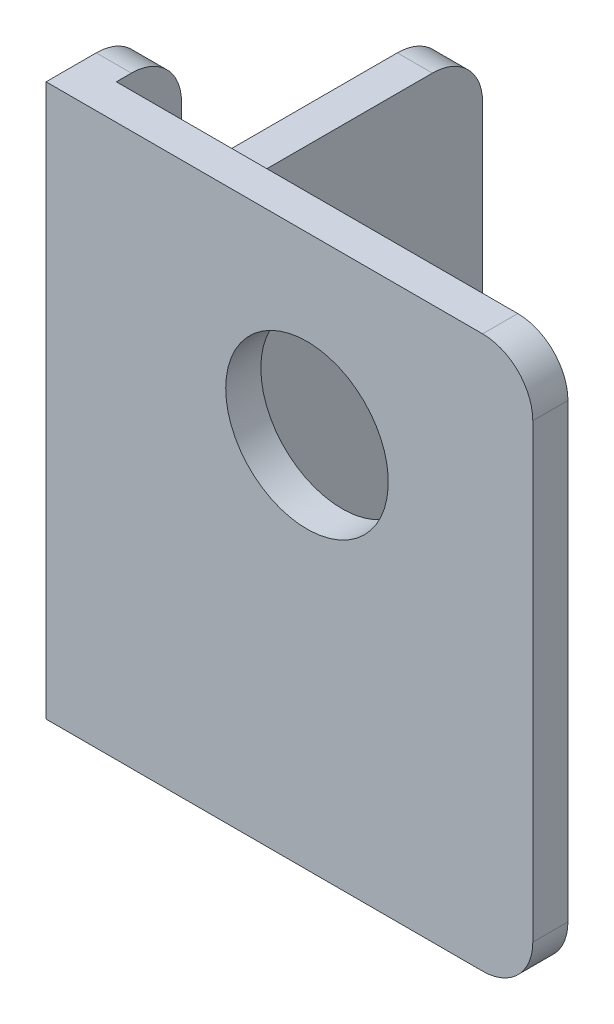
SolidWorks part; units mm, degrees
ref_plane "Front Plane" through (0, 0, 0) normal (0, 0, 1) x (1, 0, 0)
ref_plane "Top Plane" through (0, 0, 0) normal (0, 1, 0) x (1, 0, 0)
ref_plane "Right Plane" through (0, 0, 0) normal (1, 0, 0) x (0, 0, -1)
sketch "Sketch1" plane through (0, 0, 0) normal (0, 1, 0) x (1, 0, 0)
  line L0 (0, 0) -> (0, 40)
  line L1 (0, 40) -> (3.5, 40)
  line L2 (3.5, 40) -> (3.5, 3.5)
  line L3 (3.5, 3.5) -> (48.5, 3.5)
  line L4 (48.5, 3.5) -> (48.5, 0)
  line L5 (48.5, 0) -> (0, 0)
  dimension "D1" = 3.5
  dimension "D2" = 45
  dimension "D3" = 40
extrude "Boss-Extrude1" add sketch "Sketch1" along normal mid plane 55
sketch "Sketch4" plane through (0, 0, -3.5) normal (0, 0, -1) x (-1, 0, 0)
  line L0 (-26, 10) -> (-26, 27.5) construction
  line L1 (-48.5, 27.5) -> (-3.5, 27.5) construction
  line L2 (-48.5, -27.5) -> (-3.5, -27.5) construction
  circle A0 centre (-26, 10) radius 8.1
  dimension "D1" = 16.2
  dimension "D2" = 37.5
extrude "Cut-Extrude1" cut sketch "Sketch4" against normal through all
hole_wizard "M5 Clearance Hole1" positions "Sketch5" profile "Sketch6" hole size "M5" standard "ANSI Metric" end condition through all
sketch "Sketch5" plane through (0, 0, 0) normal (-1, 0, 0) x (0, 0, 1)
  line L5 (-33, -17.5) -> (-10.5, -17.5) construction
  line L7 (-40, -27.5) -> (0, -27.5) construction
  line L8 (-40, 27.5) -> (-40, -27.5) construction
  line L9 (0, 27.5) -> (0, -27.5) construction
  point P33 (-33, -17.5)
  point P36 (-10.5, -17.5)
  dimension "D1" = 10
  dimension "D2" = 7
  dimension "D3" = 10.5
sketch "Sketch6" plane through (0, -17.5, -10.5) normal (0, 1, 0) x (0, 0, 1)
  line L0 (0, 0) -> (0, 48.5)
  line L1 (0, 48.5) -> (2.75, 48.5)
  line L2 (2.75, 48.5) -> (2.75, 0)
  line L5 (2.75, 0) -> (0, 0)
  line L11 (0, -6.35) -> (0, 107.95) construction
  dimension "Thru Hole Dia." = 5.5
  dimension "Thru Hole Depth" = 48.5
sketch "Sketch7" plane through (3.5, 0, 0) normal (1, 0, 0) x (0, 0, -1)
  line L1 (40, 27.5) -> (10, 27.5)
  line L2 (40, 27.5) -> (40, 12.5)
  line L3 (40, 12.5) -> (10, 12.5)
  line L4 (10, 27.5) -> (10, 12.5)
  dimension "D1" = 30
  dimension "D2" = 15
extrude "Cut-Extrude2" cut sketch "Sketch7" against normal through all
fillet "Fillet1" radius 5 6 edges at (1.75, 12.5, -10) (1.75, 12.5, -40) (1.75, 27.5, -10) (1.75, -27.5, -40) (48.5, -27.5, -1.75) (48.5, 27.5, -1.75)
